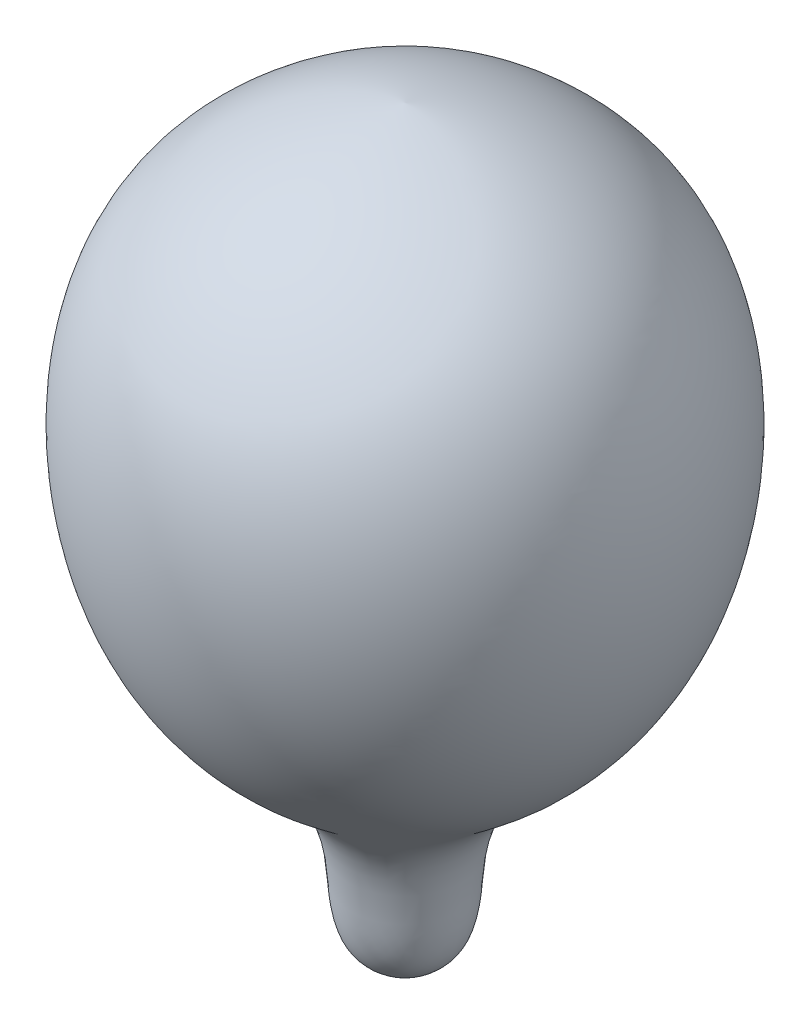
SolidWorks part; units mm, degrees
material "Balloon"
ref_plane "Front Plane" through (0, 0, 0) normal (0, 0, 1) x (1, 0, 0)
ref_plane "Top Plane" through (0, 0, 0) normal (0, 1, 0) x (1, 0, 0)
ref_plane "Right Plane" through (0, 0, 0) normal (1, 0, 0) x (0, 0, -1)
sketch "Sketch1" plane through (0, 0, 0) normal (0, 0, 1) x (1, 0, 0)
  line L0 (0, 726.9418) -> (0, 0) construction
  line L1 (0, 501.6693) -> (0, 0)
  spline S0 degree 3 poles (0, 501.6693) (50.7903, 496.0391) (163.9028, 443.638) (181.8308, 267.5188) (121.3365, 151.5224) (45.7734, 107.7227) (33.819, 46.6043) (37.7048, 6.9457) (0, 0) knots 0 0 0 0 0.244028 0.505634 0.717448 0.831784 0.876368 1 1 1 1
  point P0 (0, 319.2646)
  point P19 (0, -25.4)
  dimension "D2" = 32.1144
  dimension "D3" = 37.9363
  dimension "D4" = 44.8425
  dimension "D5" = 54.0328
  dimension "D6" = 97.4245
  dimension "D7" = 136.5672
  dimension "D8" = 164.5839
  dimension "D9" = 24.5154
  dimension "D10" = 63.4731
  dimension "D11" = 91.407
  dimension "D12" = 143.1811
  dimension "D13" = 262.2526
  dimension "D14" = 428.7544
  dimension "D15" = 488.4792
  dimension "D16" = 501.6693
  dimension "D17" = 25.4
revolve "Revolve4" add sketch "Sketch1" angle 360 about L0
